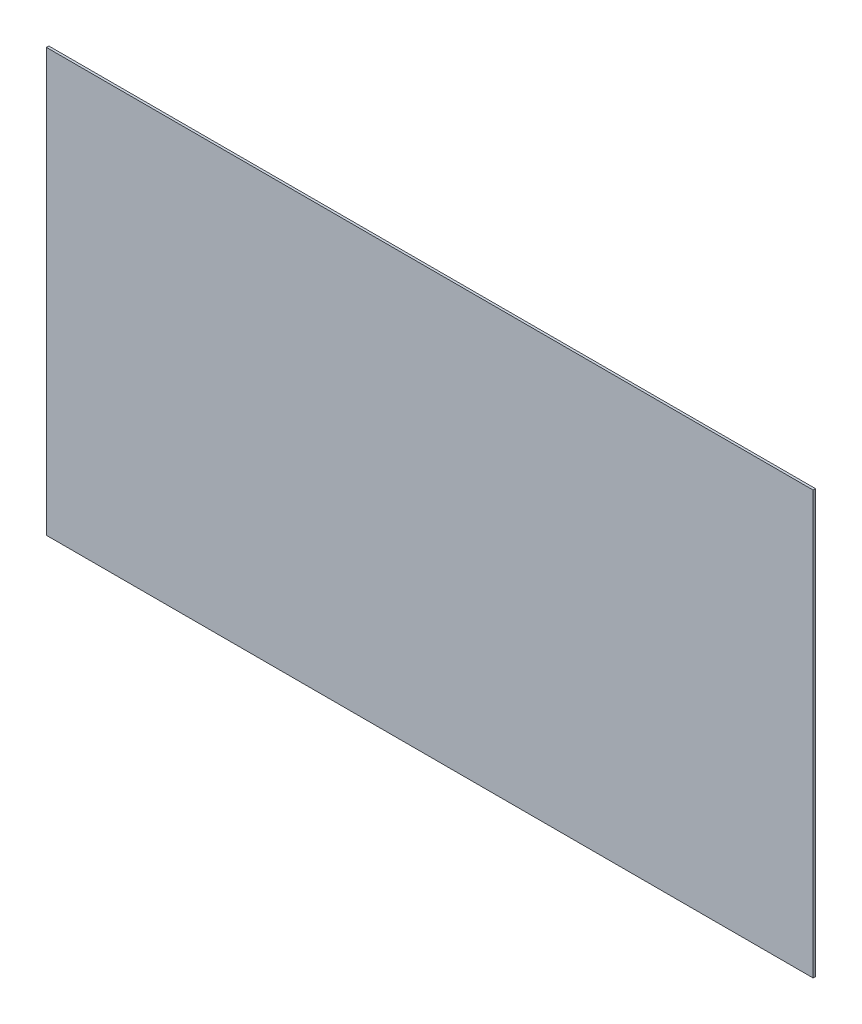
SolidWorks part; units mm, degrees
ref_plane "前视基准面" through (0, 0, 0) normal (0, 0, 1) x (1, 0, 0)
ref_plane "上视基准面" through (0, 0, 0) normal (0, 1, 0) x (1, 0, 0)
ref_plane "右视基准面" through (0, 0, 0) normal (1, 0, 0) x (0, 0, -1)
sketch "草图1" plane through (0, 0, 0) normal (0, 0, 1) x (1, 0, 0)
  line L1 (0, 0) -> (635, 0)
  line L2 (0, 0) -> (0, 350)
  line L3 (0, 350) -> (635, 350)
  line L4 (635, 0) -> (635, 350)
  dimension "D1" = 350
  dimension "D2" = 635
extrude "凸台-拉伸1" add sketch "草图1" along normal blind 2
